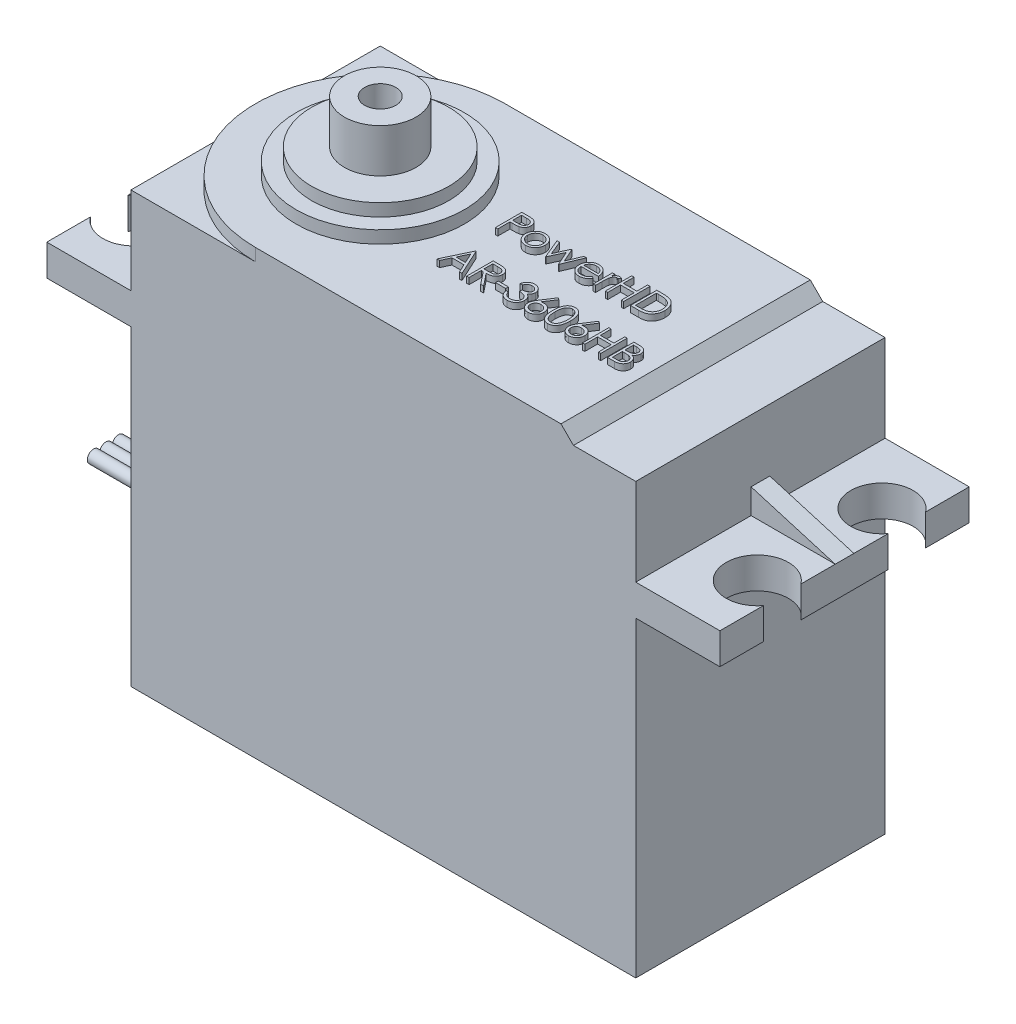
SolidWorks part; units mm, degrees
ref_plane "Ön Düzlem" through (0, 0, 0) normal (0, 0, 1) x (1, 0, 0)
ref_plane "Üst Düzlem" through (0, 0, 0) normal (0, 1, 0) x (1, 0, 0)
ref_plane "Sağ Düzlem" through (0, 0, 0) normal (1, 0, 0) x (0, 0, -1)
sketch "Çizim1" plane through (0, 0, 0) normal (0, 0, 1) x (1, 0, 0)
  line L0 (0, 0) -> (0, 26)
  line L1 (0, 26) -> (-6.75, 26)
  line L2 (-6.75, 26) -> (-6.75, 28.5)
  line L3 (-6.75, 28.5) -> (0, 28.5)
  line L4 (0, 28.5) -> (0, 35.5)
  line L5 (0, 35.5) -> (40.5, 35.5)
  line L6 (40.5, 35.5) -> (40.5, 28.5)
  line L7 (40.5, 28.5) -> (47.25, 28.5)
  line L8 (47.25, 28.5) -> (47.25, 26)
  line L9 (47.25, 26) -> (40.5, 26)
  line L10 (40.5, 26) -> (40.5, 0)
  line L11 (40.5, 0) -> (0, 0)
  dimension "D1" = 2.5
  dimension "D2" = 2.5
  dimension "D3" = 35.5
  dimension "D4" = 40.5
  dimension "D5" = 7
  dimension "D6" = 7
  dimension "D8" = 54
extrude "Yükseklik-Ekstrüzyon1" add sketch "Çizim1" along normal blind 20
sketch "Çizim2" plane through (0, 35.5, 0) normal (0, 1, 0) x (1, 0, 0)
  line L0 (0, -20) -> (0, 0) construction
  line L1 (40.5, 0) -> (0, 0) construction
  line L2 (35.5, 0) -> (35.5, -20)
  line L3 (40.5, -20) -> (0, -20) construction
  line L4 (40.5, -20) -> (40.5, 0) construction
  line L5 (35.5, 0) -> (10, 0)
  line L6 (35.5, -20) -> (10, -20)
  arc A0 (10, 0) -> (10, -20) centre (10, -10) ccw
  dimension "D1" = 20
  dimension "D2" = 5
extrude "Yükseklik-Ekstrüzyon2" add sketch "Çizim2" along normal blind 1
sketch "Çizim3" plane through (0, 36.5, 0) normal (0, 1, 0) x (1, 0, 0)
  circle A0 centre (10, -10) radius 6.75
  dimension "D1" = 13.5
extrude "Yükseklik-Ekstrüzyon3" add sketch "Çizim3" along normal blind 1
sketch "Çizim4" plane through (0, 37.5, 0) normal (0, 1, 0) x (1, 0, 0)
  circle A0 centre (10, -10) radius 5.5
  dimension "D1" = 11
extrude "Yükseklik-Ekstrüzyon4" add sketch "Çizim4" along normal blind 1
sketch "Çizim5" plane through (0, 38.5, 0) normal (0, 1, 0) x (1, 0, 0)
  circle A0 centre (10, -10) radius 2.875
  circle A1 centre (10, -10) radius 1.25
  dimension "D1" = 5.75
  dimension "D2" = 2.5
extrude "Yükseklik-Ekstrüzyon5" add sketch "Çizim5" along normal blind 3.5
sketch "Çizim6" plane through (0, 0, 20) normal (0, 0, 1) x (1, 0, 0)
  line L0 (35.5, 35.5) -> (35.5, 36.5)
  line L1 (35.5, 36.5) -> (34.5, 36.5)
  line L2 (10, 36.5) -> (35.5, 36.5) construction
  line L3 (34.5, 36.5) -> (35.5, 35.5)
  dimension "D1" = 1
extrude "Kes-Ekstrüzyon1" cut sketch "Çizim6" against normal through all
sketch "Çizim7" plane through (0, 28.5, 0) normal (0, 1, 0) x (1, 0, 0)
  line L0 (-6.75, -20) -> (-6.75, 0) construction
  line L1 (20.25, 12.0535) -> (20.25, -28.4025) construction
  circle A0 centre (-4.75, -5) radius 2.5
  circle A1 centre (-4.75, -15) radius 2.5
  circle A2 centre (45.25, -15) radius 2.5
  circle A3 centre (45.25, -5) radius 2.5
  point P0 (-6.75, -10)
  point P13 (47.25, -10)
  dimension "D5" = 5
  dimension "D6" = 5
  dimension "D1" = 5
  dimension "D2" = 5
  dimension "D3" = 2
  dimension "D4" = 2
  dimension "D7" = 27
extrude "Kes-Ekstrüzyon2" cut sketch "Çizim7" against normal blind 3.5
ref_plane "Düzlem1" through (0, 0, 10) normal (0, 0, 1) x (1, 0, 0)
sketch "Çizim12" plane through (0, 0, 10) normal (0, 0, 1) x (1, 0, 0)
  line L0 (-6.75, 28.5) -> (0, 30.5)
  line L3 (0, 35.5) -> (0, 28.5) construction
  line L5 (10, 35.5) -> (0, 35.5) construction
  line L6 (0, 28.5) -> (-6.75, 28.5) construction
  dimension "D2" = 5
rib "Feder14" sketch "Çizim12" sketch "Çizim12" thickness 1.5 extrusion direction parallel to sketch draft on no parameters "D1"=1.5
sketch "Çizim13" plane through (0, 0, 10) normal (0, 0, 1) x (1, 0, 0)
  line L0 (47.25, 28.5) -> (40.5, 30.5)
  line L1 (40.5, 28.5) -> (40.5, 35.5) construction
  line L2 (40.5, 35.5) -> (35.5, 35.5) construction
  dimension "D1" = 5
rib "Feder16" sketch "Çizim13" sketch "Çizim13" thickness 1.5 extrusion direction parallel to sketch draft on no parameters "D1"=1.5
sketch "Çizim14" plane through (0, 0, 0) normal (-1, 0, 0) x (0, 0, 1)
  line L0 (20, 0) -> (0, 0) construction
  circle A0 centre (10, 15) radius 2.25
  dimension "D1" = 4.5
  dimension "D2" = 15
extrude "Kes-Ekstrüzyon3" cut sketch "Çizim14" against normal blind 7
sketch "Çizim15" plane through (0, 0, 0) normal (-1, 0, 0) x (0, 0, 1)
  line L0 (0, 26) -> (0, 0) construction
  line L1 (6.5, 8) -> (13.5, 8)
  line L2 (6.5, 8) -> (6.5, 5)
  line L3 (6.5, 5) -> (13.5, 5)
  line L4 (13.5, 8) -> (13.5, 5)
  line L5 (20, 0) -> (0, 0) construction
  dimension "D1" = 7
  dimension "D2" = 3
  dimension "D3" = 6.5
  dimension "D4" = 5
extrude "Yükseklik-Ekstrüzyon6" add sketch "Çizim15" along normal blind 6
sketch "Çizim16" plane through (-6, 0, 0) normal (-1, 0, 0) x (0, 0, 1)
  line L2 (6.5, 8) -> (6.5, 5) construction
  line L3 (6.5, 5) -> (13.5, 5) construction
  circle A0 centre (9, 6.5) radius 0.5
  circle A1 centre (10, 6.5) radius 0.5
  circle A2 centre (11, 6.5) radius 0.5
  point P10 (8.5, 6.5)
  dimension "D1" = 1
  dimension "D2" = 2
  dimension "D3" = 1.5
extrude "Yükseklik-Ekstrüzyon8" add sketch "Çizim16" along normal blind 6 separate body contours A0 | A1 | A2
chamfer "Pah1" distance 1 angle 45 4 edges at (0, 0, 10) (20.25, 0, 20) (40.5, 0, 10) (20.25, 0, 0)
sketch "Çizim17" plane through (0, 36.5, 0) normal (0, 1, 0) x (1, 0, 0)
  text T0 "PowerHD \r\nAR-3606HB" font "Century Gothic" height in points 8
extrude "Yükseklik-Ekstrüzyon9" add sketch "Çizim17" along normal blind 0.5
